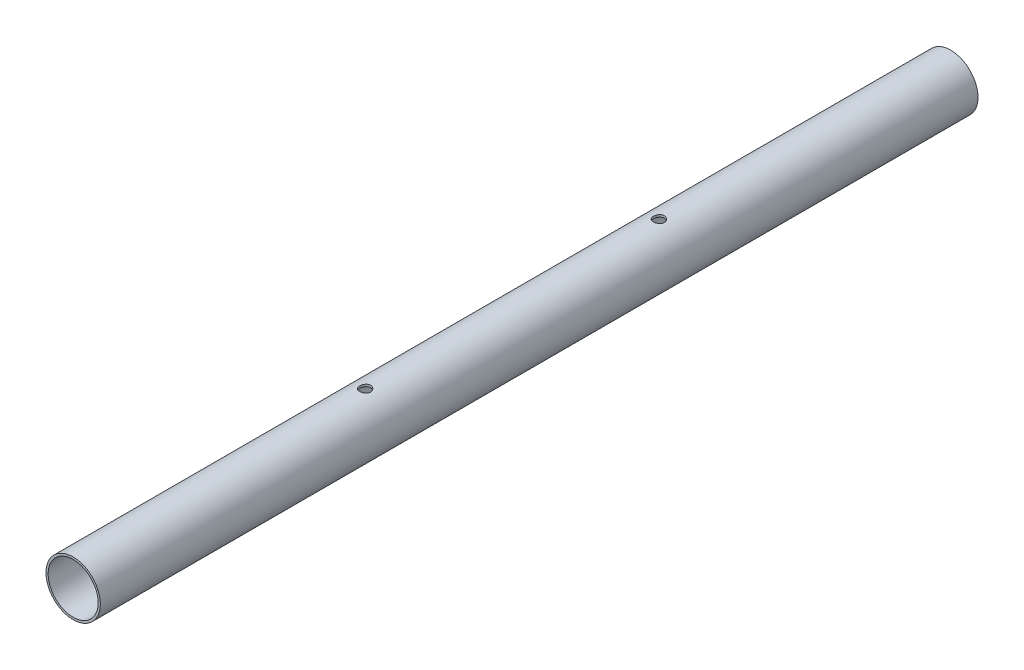
SolidWorks part; units mm, degrees
material "Thornel Mat VMA"
ref_plane "前视基准面" through (0, 0, 0) normal (0, 0, 1) x (1, 0, 0)
ref_plane "上视基准面" through (0, 0, 0) normal (0, 1, 0) x (1, 0, 0)
ref_plane "右视基准面" through (0, 0, 0) normal (1, 0, 0) x (0, 0, -1)
other "Configuration Table"
sketch "草图1" plane through (0, 0, 0) normal (0, 0, 1) x (1, 0, 0)
  circle A0 centre (0, 0) radius 12.5
  circle A1 centre (0, 0) radius 11.5
  dimension "D1" = 25
  dimension "D2" = 1
extrude "凸台-拉伸1" add sketch "草图1" along normal mid plane 403.4
sketch "草图3" plane through (0, 0, 0) normal (0, 1, 0) x (1, 0, 0)
  line L0 (0, 0) -> (52.6749, 0) construction
  circle A0 centre (0, 67.5) radius 2.5 construction
  circle A1 centre (0, 67.5) radius 2.5
  circle A2 centre (0, -67.5) radius 2.5
extrude "切除-拉伸1" cut sketch "草图3" against normal mid plane 100
sketch "草图4" plane through (0, 0, 0) normal (1, 0, 0) x (0, 0, -1)
  line L0 (-201.7, 0) -> (201.7, 0)
  line L1 (-201.7, 12.5) -> (-201.7, -12.5) construction
  line L2 (201.7, -12.5) -> (201.7, 12.5) construction
